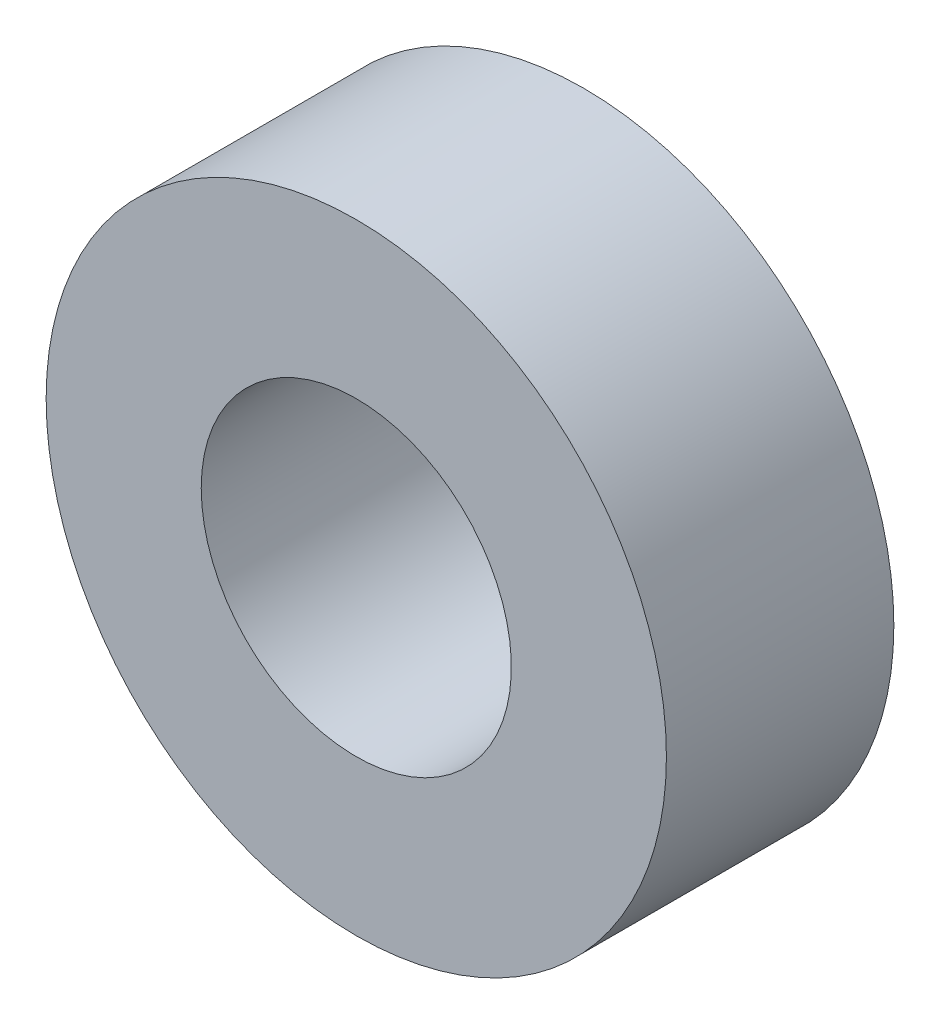
SolidWorks part; units mm, degrees
material "Pine"
ref_plane "Front Plane" through (0, 0, 0) normal (0, 0, 1) x (1, 0, 0)
ref_plane "Top Plane" through (0, 0, 0) normal (0, 1, 0) x (1, 0, 0)
ref_plane "Right Plane" through (0, 0, 0) normal (1, 0, 0) x (0, 0, -1)
other "Configuration Table"
sketch "Sketch1" plane through (0, 0, 0) normal (0, 0, 1) x (1, 0, 0)
  circle A0 centre (0, 0) radius 25.4
  circle A1 centre (0, 0) radius 9.525
  dimension "D1" = 50.8
  dimension "D2" = 19.05
extrude "Boss-Extrude1" [suppressed] add sketch "Sketch1" along normal blind 50.8
sketch "Sketch2" plane through (0, 0, 0) normal (0, 0, 1) x (1, 0, 0)
  circle A2 centre (0, 0) radius 6.35
  circle A3 centre (0, 0) radius 25.4
  dimension "D1" = 12.7
  dimension "D2" = 50.8
extrude "Boss-Extrude2" [suppressed] add sketch "Sketch2" along normal blind 25.4
sketch "Sketch4" plane through (0, 0, 0) normal (0, 1, 0) x (1, 0, 0)
  line L0 (0, 0) -> (0, -35.0188) construction
  line L6 (-19.05, 0) -> (-9.525, 0)
  line L7 (-19.05, 0) -> (-19.05, -25.4)
  line L8 (-19.05, -25.4) -> (-9.525, -25.4)
  line L9 (-9.525, 0) -> (-9.525, -25.4)
  dimension "D1" = 25.4
  dimension "D2" = 38.1
  dimension "D3" = 19.05
revolve "Revolve2" [suppressed] add sketch "Sketch4" angle 360 about L0
sketch "Sketch5" [suppressed] plane through (0, 0, 0) normal (0, 0, 1) x (1, 0, 0)
  circle A0 centre (0, 0) radius 9.525
  circle A1 centre (0, 0) radius 19.05
  dimension "D1" = 19.05
  dimension "D2" = 38.1
extrude "Boss-Extrude3" [suppressed] add sketch "Sketch5" along normal blind 12.7
sketch "Sketch7" [suppressed] plane through (0, 0, 0) normal (1, 0, 0) x (0, 0, -1)
  line L0 (0, 0) -> (-69.6482, 0) construction
  line L2 (-28.575, -25.5225) -> (-22.225, -25.5225)
  line L3 (-28.575, -25.5225) -> (-28.575, -21.5601)
  line L4 (-28.575, -21.5601) -> (-22.225, -21.5601)
  line L5 (-22.225, -25.5225) -> (-22.225, -21.5601)
  point P9 (-25.4, -25.5225)
  dimension "D1" = 3.9624
  dimension "D2" = 6.35
  dimension "D3" = 25.4
revolve "Cut-Revolve1" [suppressed] cut sketch "Sketch7" angle 360 about L0
sketch "Sketch8" plane through (0, 0, 0) normal (0, 1, 0) x (1, 0, 0)
  line L0 (0, 0) -> (0, -14.4938) construction
  line L1 (-19.05, 0) -> (-9.525, 0)
  line L2 (-9.525, 0) -> (-9.525, -13.97)
  line L3 (-9.525, -13.97) -> (-19.05, -13.97)
  line L4 (-19.05, -13.97) -> (-19.05, 0)
  dimension "D1" = 38.1
  dimension "D2" = 19.05
  dimension "D3" = 13.97
revolve "Revolve3" add sketch "Sketch8" angle 360 about L0
sketch "Sketch9" plane through (0, 0, 13.97) normal (0, 0, 1) x (1, 0, 0)
  line L0 (0, 0) -> (19.05, 0)
  circle A0 centre (0, 0) radius 19.05 construction
sketch "Sketch10" [suppressed] plane through (0, 0, 50.8) normal (0, 0, 1) x (1, 0, 0)
  line L0 (0, 0) -> (-39.5922, 0)
